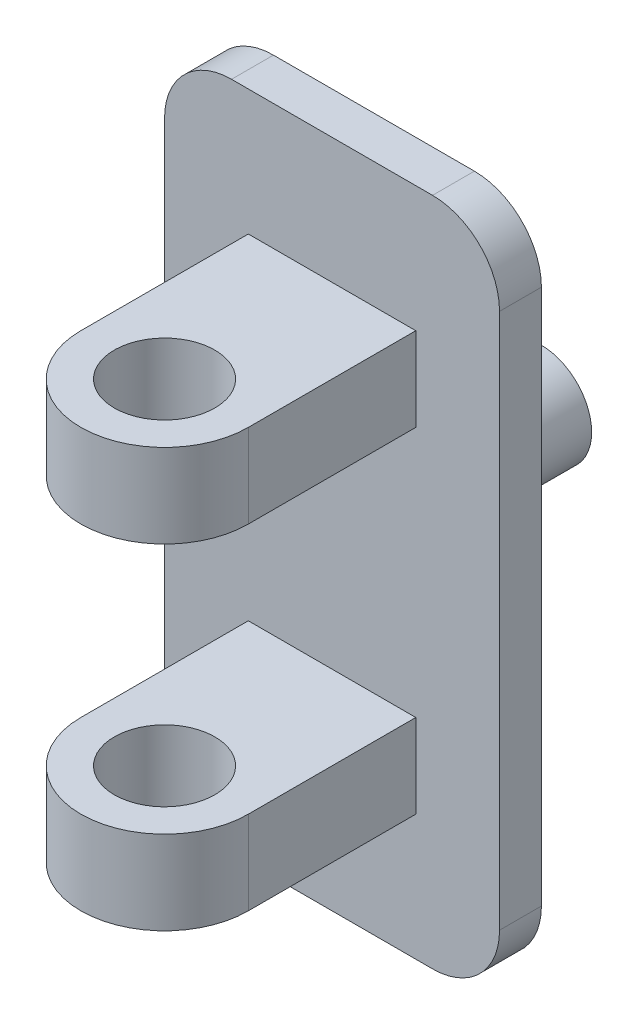
SolidWorks part; units mm, degrees
material "1060 Alloy"
ref_plane "Front Plane" through (0, 0, 0) normal (0, 0, 1) x (1, 0, 0)
ref_plane "Top Plane" through (0, 0, 0) normal (0, 1, 0) x (1, 0, 0)
ref_plane "Right Plane" through (0, 0, 0) normal (1, 0, 0) x (0, 0, -1)
sketch "Sketch2" plane through (0, 0, 0) normal (0, 0, 1) x (1, 0, 0)
  circle A0 centre (0, 0) radius 1.905
  dimension "D1" = 3.81
extrude "Boss-Extrude1" add sketch "Sketch2" along normal mid plane 6.35
sketch "Sketch3" plane through (0, 0, 3.175) normal (0, 0, 1) x (1, 0, 0)
  line L1 (-6.35, -12.7) -> (6.35, -12.7)
  line L2 (-6.35, -12.7) -> (-6.35, 12.7)
  line L3 (-6.35, 12.7) -> (6.35, 12.7)
  line L4 (6.35, -12.7) -> (6.35, 12.7)
  line L5 (-6.35, -12.7) -> (6.35, 12.7) construction
  line L6 (-6.35, 12.7) -> (6.35, -12.7) construction
  point P0 (0, 0)
  dimension "D1" = 12.7
  dimension "D2" = 25.4
extrude "Boss-Extrude2" add sketch "Sketch3" along normal blind 1.5875
ref_plane "Plane1" through (0, 6.35, 0) normal (0, 1, 0) x (1, 0, 0)
sketch "Sketch5" plane through (0, 6.35, 0) normal (0, 1, 0) x (1, 0, 0)
  line L0 (-3.175, -4.7625) -> (3.175, -4.7625)
  line L1 (6.35, -4.7625) -> (-6.35, -4.7625) construction
  line L2 (3.175, -4.7625) -> (3.175, -11.1125)
  line L4 (-3.175, -11.1125) -> (-3.175, -4.7625)
  line L5 (0, -4.7625) -> (0, -14.2875) construction
  arc A0 (-3.175, -11.1125) -> (3.175, -11.1125) centre (0, -11.1125) ccw
  circle A1 centre (0, -11.1125) radius 1.905
  point P4 (0, -4.7625)
  dimension "D2" = 3.81
  dimension "D1" = 6.35
  dimension "D3" = 6.35
extrude "Boss-Extrude3" add sketch "Sketch5" along normal mid plane 3.175
mirror "Mirror1" about plane through (0, 0, 0) normal (0, 1, 0) of "Boss-Extrude3"
fillet "Fillet1" radius 2.54 4 edges at (6.35, 12.7, 3.9688) (6.35, -12.7, 3.9688) (-6.35, -12.7, 3.9688) (-6.35, 12.7, 3.9688)
